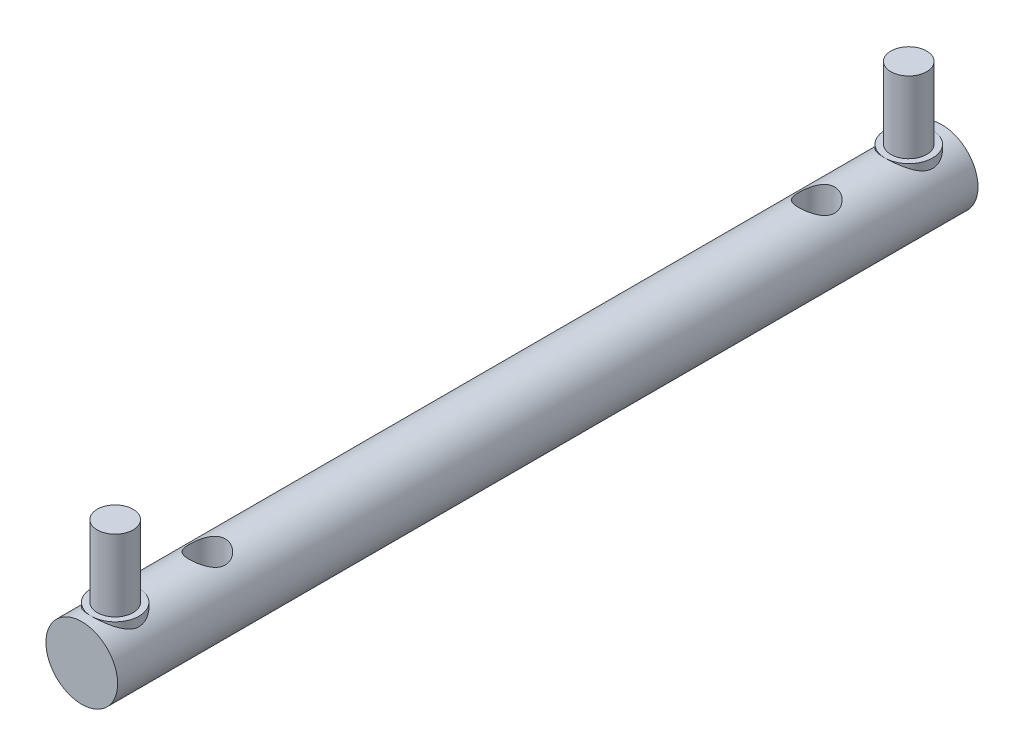
SolidWorks part; units mm, degrees
ref_plane "Front Plane" through (0, 0, 0) normal (0, 0, 1) x (1, 0, 0)
ref_plane "Top Plane" through (0, 0, 0) normal (0, 1, 0) x (1, 0, 0)
ref_plane "Right Plane" through (0, 0, 0) normal (1, 0, 0) x (0, 0, -1)
sketch "Sketch1" plane through (0, 0, 0) normal (0, 0, 1) x (1, 0, 0)
  circle A0 centre (0, 0) radius 15
  dimension "D1" = 30
extrude "Boss-Extrude1" add sketch "Sketch1" along normal blind 360
ref_plane "Plane2" through (0, 15, 0) normal (0, 1, 0) x (1, 0, 0)
sketch "Sketch2" plane through (0, 15, 0) normal (0, 1, 0) x (1, 0, 0)
  line L2 (-15, -360) -> (15, -360) construction
  line L3 (15, 0) -> (-15, 0) construction
  circle A0 centre (0, -13.965) radius 7.5
  circle A1 centre (0, -346.035) radius 7.5
  dimension "D1" = 15
  dimension "D2" = 15
  dimension "D3" = 332.07
  dimension "D4" = 13.965
  dimension "D5" = 13.965
extrude "Boss-Extrude2" add sketch "Sketch2" against normal blind 10
sketch "Sketch3" plane through (0, 15, 0) normal (0, 1, 0) x (1, 0, 0)
  circle A0 centre (0, -346.035) radius 7.5
  circle A1 centre (0, -13.965) radius 7.5
  dimension "D1" = 15
  dimension "D2" = 15
  dimension "D3" = 332.07
extrude "Boss-Extrude3" add sketch "Sketch3" along normal blind 30
sketch "Sketch8" plane through (0, 15, 0) normal (0, 1, 0) x (1, 0, 0)
  circle A0 centre (0, -13.965) radius 10
  circle A1 centre (0, -346.035) radius 10
  dimension "D1" = 20
  dimension "D2" = 20
extrude "Boss-Extrude4" add sketch "Sketch8" against normal blind 10
sketch "Sketch9" plane through (0, 15, 0) normal (0, 1, 0) x (1, 0, 0)
  line L1 (15, 0) -> (-15, 0) construction
  circle A0 centre (0, -52.47) radius 7.5
  circle A1 centre (0, -307.47) radius 7.5
  dimension "D1" = 15
  dimension "D2" = 15
  dimension "D3" = 255
  dimension "52.47" = 52.47
extrude "Cut-Extrude1" cut sketch "Sketch9" against normal through all
